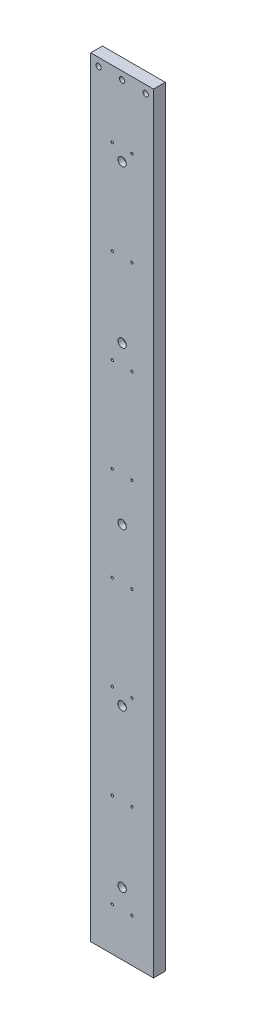
SolidWorks part; units mm, degrees
ref_plane "Front" through (0, 0, 0) normal (0, 0, 1) x (1, 0, 0)
ref_plane "Top" through (0, 0, 0) normal (0, 1, 0) x (1, 0, 0)
ref_plane "Right" through (0, 0, 0) normal (1, 0, 0) x (0, 0, -1)
sketch "Sketch1" plane through (0, 0, 0) normal (0, 0, 1) x (1, 0, 0)
  line L1 (0, 0) -> (101.6, 0)
  line L2 (0, 0) -> (0, 1244.6)
  line L3 (0, 1244.6) -> (101.6, 1244.6)
  line L4 (101.6, 0) -> (101.6, 1244.6)
  dimension "D1" = 101.6
  dimension "D2" = 1244.6
extrude "Extrude1" add sketch "Sketch1" along normal blind 19.05
hole_wizard "CBORE for 5/16 Socket Head Cap Screw1" positions "Sketch3" profile "Sketch2" counterbore size "5/16" standard "Ansi Inch" end condition through all
sketch "Sketch3" plane through (0, 0, 19.05) normal (0, 0, 1) x (1, 0, 0)
  line L0 (0, 0) -> (101.6, 0) construction
  line L1 (0, 1244.6) -> (0, 0) construction
  point P0 (50.8, 101.6)
  point P6 (50.8, 355.6)
  point P8 (50.8, 609.6)
  point P10 (50.8, 863.6)
  point P12 (50.8, 1117.6)
  dimension "D1" = 101.6
  dimension "D2" = 50.8
  dimension "D3" = 254
  dimension "D7" = 508
  dimension "D8" = 762
  dimension "D9" = 1016
sketch "Sketch2" plane through (50.8, 101.6, 19.05) normal (1, 0, 0) x (0, -1, 0)
  line L0 (0, 0) -> (0, 19.05)
  line L1 (0, 19.05) -> (4.365, 19.05)
  line L3 (4.365, 19.05) -> (4.365, 8.6995)
  line L4 (4.365, 8.6995) -> (6.7475, 8.6995)
  line L5 (6.7475, 8.6995) -> (6.7475, 0)
  line L7 (6.7475, 0) -> (0, 0)
  line L11 (0, -6.35) -> (0, 107.95) construction
  dimension "Thru Hole Dia." = 8.73
  dimension "Thru Hole Depth" = 19.05
  dimension "C'Bore Dia." = 13.495
  dimension "C'Bore Depth" = 8.6995
hole_wizard "5/16-18 Tapped Hole1" positions "Sketch5" profile "Sketch4" tap size "5/16-18" standard "Ansi Inch"
sketch "Sketch5" plane through (0, 0, 0) normal (0, -1, 0) x (1, 0, 0)
  line L0 (0, 0) -> (101.6, 0) construction
  line L1 (0, 19.05) -> (0, 0) construction
  point P0 (12.7, 9.525)
  point P1 (88.9, 9.525)
  dimension "D1" = 9.525
  dimension "D2" = 12.7
  dimension "D3" = 76.2
sketch "Sketch4" plane through (12.7, 0, 9.525) normal (1, 0, 0) x (0, 0, -1)
  line L0 (0, 0) -> (0, 24.8846)
  line L1 (0, 24.8846) -> (3.2639, 22.9235)
  line L2 (3.2639, 22.9235) -> (3.2639, 0)
  line L5 (3.2639, 0) -> (0, 0)
  line L10 (0, 24.8846) -> (-3.2639, 22.9235) construction
  line L11 (0, -6.35) -> (0, 107.95) construction
  dimension "Tap Drill Dia." = 6.5278
  dimension "Tap Drill Depth" = 22.9235
  dimension "Drill Angle" = 118
cosmetic thread "Hole Thread12" parameters "D1"=15.875, "D2"=7.9375
cosmetic thread "Hole Thread13" parameters "D1"=15.875, "D2"=7.9375
hole_wizard "#10-24 Tapped Hole1" positions "Sketch7" profile "Sketch6" tap size "#10-24" standard "Ansi Inch" end condition through all
sketch "Sketch7" plane through (0, 0, 19.05) normal (0, 0, 1) x (1, 0, 0)
  circle A0 centre (50.8, 101.6) radius 4.365 construction
  point P0 (34.925, 69.85)
  point P1 (66.675, 69.85)
  dimension "D2" = 15.875
  dimension "D1" = 31.75
  dimension "D3" = 31.75
sketch "Sketch6" plane through (34.925, 69.85, 19.05) normal (1, 0, 0) x (0, -1, 0)
  line L0 (0, 0) -> (0, 19.05)
  line L1 (0, 19.05) -> (1.8986, 19.05)
  line L2 (1.8986, 19.05) -> (1.8986, 0)
  line L5 (1.8986, 0) -> (0, 0)
  line L11 (0, -6.35) -> (0, 107.95) construction
  dimension "Thru Tap Drill Dia." = 3.7973
  dimension "Thru Tap Drill Depth" = 19.05
cosmetic thread "Hole Thread10" parameters "D2"=4.826
cosmetic thread "Hole Thread11" parameters "D2"=4.826
pattern_linear "LPattern1" count 8 spacing 152.4 along (0, 1, 0) of "#10-24 Tapped Hole1"
hole_wizard "5/16 Clearance Hole1" positions "Sketch9" profile "Sketch8" hole size "5/16" standard "Ansi Inch" end condition through all
sketch "Sketch9" plane through (0, 0, 19.05) normal (0, 0, 1) x (1, 0, 0)
  circle A0 centre (50.8, 101.6) radius 6.7475 construction
  circle A1 centre (50.8, 1117.6) radius 6.7475 construction
  point P0 (50.8, 1231.9)
  point P1 (12.7, 1231.9)
  point P11 (88.9, 1231.9)
  dimension "D1" = 38.1
  dimension "D2" = 1130.3
  dimension "D3" = 38.1
sketch "Sketch8" plane through (50.8, 1231.9, 19.05) normal (1, 0, 0) x (0, -1, 0)
  line L0 (0, 0) -> (0, 19.05)
  line L1 (0, 19.05) -> (4.365, 19.05)
  line L2 (4.365, 19.05) -> (4.365, 0)
  line L5 (4.365, 0) -> (0, 0)
  line L11 (0, -6.35) -> (0, 107.95) construction
  dimension "Thru Hole Dia." = 8.73
  dimension "Thru Hole Depth" = 19.05
